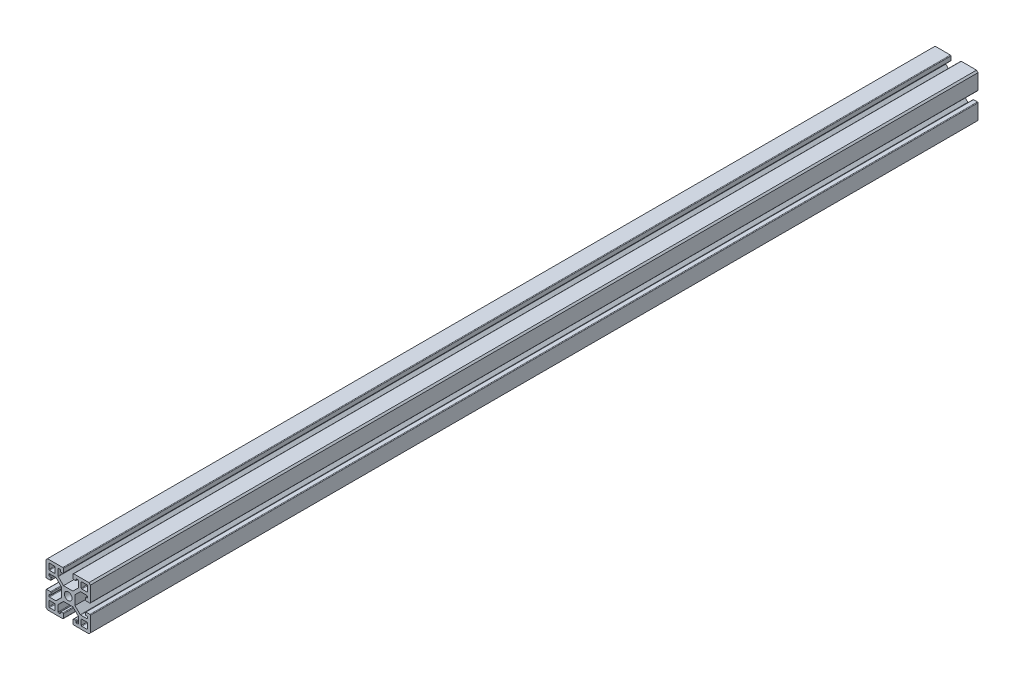
SolidWorks part; units mm, degrees
ref_plane "Front" through (0, 0, 0) normal (0, 0, 1) x (1, 0, 0)
ref_plane "Top" through (0, 0, 0) normal (0, 1, 0) x (1, 0, 0)
ref_plane "Right" through (0, 0, 0) normal (1, 0, 0) x (0, 0, -1)
sketch "Sketch1" plane through (0, 0, 0) normal (0, 0, 1) x (1, 0, 0)
  line L0 (4.699, 19.05) -> (17.78, 19.05)
  line L1 (4.191, 15.24) -> (4.191, 18.542)
  line L2 (6.223, 14.732) -> (4.699, 14.732)
  line L3 (6.731, 16.002) -> (6.731, 15.24)
  line L4 (0, 0) -> (18.415, 18.415) construction
  line L5 (8.1534, 16.51) -> (7.239, 16.51)
  line L6 (8.6614, 10.6679) -> (8.6614, 16.002)
  line L7 (4.0459, 5.842) -> (8.5126, 10.3087)
  line L8 (-4.0459, 5.842) -> (4.0459, 5.842)
  line L9 (11.2014, 16.002) -> (11.2014, 11.7094)
  line L10 (16.002, 16.51) -> (11.7094, 16.51)
  line L11 (-19.05, 17.78) -> (-17.78, 19.05)
  line L12 (-19.05, 4.699) -> (-19.05, 17.78)
  line L13 (-15.24, 4.191) -> (-18.542, 4.191)
  line L14 (16.51, 16.002) -> (16.51, 11.7094)
  line L15 (16.002, 11.2014) -> (11.7094, 11.2014)
  line L16 (-14.732, 6.223) -> (-14.732, 4.699)
  line L17 (-16.002, 6.731) -> (-15.24, 6.731)
  line L18 (-16.51, 8.1534) -> (-16.51, 7.239)
  line L19 (-10.6679, 8.6614) -> (-16.002, 8.6614)
  line L20 (-5.842, 4.0459) -> (-10.3087, 8.5126)
  line L21 (-5.842, -4.0459) -> (-5.842, 4.0459)
  line L22 (-16.002, 11.2014) -> (-11.7094, 11.2014)
  line L23 (-16.51, 16.002) -> (-16.51, 11.7094)
  line L24 (-16.002, 16.51) -> (-11.7094, 16.51)
  line L25 (-11.2014, 16.002) -> (-11.2014, 11.7094)
  line L26 (-4.0459, 5.842) -> (-8.5126, 10.3087)
  line L27 (-8.6614, 10.6679) -> (-8.6614, 16.002)
  line L28 (-8.1534, 16.51) -> (-7.239, 16.51)
  line L29 (-6.731, 16.002) -> (-6.731, 15.24)
  line L30 (-6.223, 14.732) -> (-4.699, 14.732)
  line L31 (-4.191, 15.24) -> (-4.191, 18.542)
  line L32 (0, 0) -> (0, 21.3525) construction
  line L33 (0, 0) -> (24.5779, 0) construction
  line L34 (-4.699, 19.05) -> (-17.78, 19.05)
  line L35 (19.05, -17.78) -> (17.78, -19.05)
  line L36 (19.05, -4.699) -> (19.05, -17.78)
  line L37 (15.24, -4.191) -> (18.542, -4.191)
  line L38 (14.732, -6.223) -> (14.732, -4.699)
  line L39 (16.002, -6.731) -> (15.24, -6.731)
  line L40 (16.51, -8.1534) -> (16.51, -7.239)
  line L41 (10.6679, -8.6614) -> (16.002, -8.6614)
  line L42 (5.842, -4.0459) -> (10.3087, -8.5126)
  line L43 (-4.699, -19.05) -> (-17.78, -19.05)
  line L44 (-4.191, -15.24) -> (-4.191, -18.542)
  line L45 (-6.223, -14.732) -> (-4.699, -14.732)
  line L46 (-6.731, -16.002) -> (-6.731, -15.24)
  line L47 (-8.1534, -16.51) -> (-7.239, -16.51)
  line L48 (-8.6614, -10.6679) -> (-8.6614, -16.002)
  line L49 (-4.0459, -5.842) -> (-8.5126, -10.3087)
  line L50 (-11.2014, -16.002) -> (-11.2014, -11.7094)
  line L51 (-16.002, -16.51) -> (-11.7094, -16.51)
  line L52 (-16.51, -16.002) -> (-16.51, -11.7094)
  line L53 (-16.002, -11.2014) -> (-11.7094, -11.2014)
  line L54 (-5.842, -4.0459) -> (-10.3087, -8.5126)
  line L55 (-10.6679, -8.6614) -> (-16.002, -8.6614)
  line L56 (-16.51, -8.1534) -> (-16.51, -7.239)
  line L57 (-16.002, -6.731) -> (-15.24, -6.731)
  line L58 (-14.732, -6.223) -> (-14.732, -4.699)
  line L59 (16.002, -11.2014) -> (11.7094, -11.2014)
  line L60 (16.51, -16.002) -> (16.51, -11.7094)
  line L61 (-15.24, -4.191) -> (-18.542, -4.191)
  line L62 (-19.05, -4.699) -> (-19.05, -17.78)
  line L63 (-19.05, -17.78) -> (-17.78, -19.05)
  line L64 (16.002, -16.51) -> (11.7094, -16.51)
  line L65 (11.2014, -16.002) -> (11.2014, -11.7094)
  line L66 (-4.0459, -5.842) -> (4.0459, -5.842)
  line L67 (4.0459, -5.842) -> (8.5126, -10.3087)
  line L68 (8.6614, -10.6679) -> (8.6614, -16.002)
  line L69 (8.1534, -16.51) -> (7.239, -16.51)
  line L70 (6.731, -16.002) -> (6.731, -15.24)
  line L71 (6.223, -14.732) -> (4.699, -14.732)
  line L72 (4.191, -15.24) -> (4.191, -18.542)
  line L73 (4.699, -19.05) -> (17.78, -19.05)
  line L134 (5.842, -4.0459) -> (5.842, 4.0459)
  line L135 (5.842, 4.0459) -> (10.3087, 8.5126)
  line L136 (10.6679, 8.6614) -> (16.002, 8.6614)
  line L137 (16.51, 8.1534) -> (16.51, 7.239)
  line L138 (16.002, 6.731) -> (15.24, 6.731)
  line L139 (14.732, 6.223) -> (14.732, 4.699)
  line L140 (15.24, 4.191) -> (18.542, 4.191)
  line L141 (19.05, 4.699) -> (19.05, 17.78)
  line L142 (19.05, 17.78) -> (17.78, 19.05)
  arc A0 (4.191, 18.542) -> (4.699, 19.05) centre (4.699, 18.542) cw
  circle A1 centre (0, 0) radius 3.302
  arc A2 (4.699, 14.732) -> (4.191, 15.24) centre (4.699, 15.24) cw
  arc A3 (6.731, 15.24) -> (6.223, 14.732) centre (6.223, 15.24) cw
  arc A4 (6.731, 16.002) -> (7.239, 16.51) centre (7.239, 16.002) cw
  arc A5 (8.1534, 16.51) -> (8.6614, 16.002) centre (8.1534, 16.002) cw
  arc A6 (8.6614, 10.6679) -> (8.5126, 10.3087) centre (8.1534, 10.6679) cw
  arc A7 (11.2014, 16.002) -> (11.7094, 16.51) centre (11.7094, 16.002) cw
  arc A8 (-18.542, 4.191) -> (-19.05, 4.699) centre (-18.542, 4.699) cw
  arc A9 (-14.732, 4.699) -> (-15.24, 4.191) centre (-15.24, 4.699) cw
  arc A10 (-15.24, 6.731) -> (-14.732, 6.223) centre (-15.24, 6.223) cw
  arc A11 (-16.002, 6.731) -> (-16.51, 7.239) centre (-16.002, 7.239) cw
  arc A12 (-16.51, 8.1534) -> (-16.002, 8.6614) centre (-16.002, 8.1534) cw
  arc A13 (-10.6679, 8.6614) -> (-10.3087, 8.5126) centre (-10.6679, 8.1534) cw
  arc A14 (11.2014, 11.7094) -> (11.7094, 11.2014) centre (11.7094, 11.7094) ccw
  arc A15 (-16.002, 11.2014) -> (-16.51, 11.7094) centre (-16.002, 11.7094) cw
  arc A16 (16.51, 16.002) -> (16.002, 16.51) centre (16.002, 16.002) ccw
  arc A17 (16.002, 11.2014) -> (16.51, 11.7094) centre (16.002, 11.7094) ccw
  arc A18 (-16.51, 16.002) -> (-16.002, 16.51) centre (-16.002, 16.002) cw
  arc A19 (-11.2014, 11.7094) -> (-11.7094, 11.2014) centre (-11.7094, 11.7094) cw
  arc A20 (-11.2014, 16.002) -> (-11.7094, 16.51) centre (-11.7094, 16.002) ccw
  arc A21 (-8.6614, 10.6679) -> (-8.5126, 10.3087) centre (-8.1534, 10.6679) ccw
  arc A22 (-8.1534, 16.51) -> (-8.6614, 16.002) centre (-8.1534, 16.002) ccw
  arc A23 (-6.731, 16.002) -> (-7.239, 16.51) centre (-7.239, 16.002) ccw
  arc A24 (-6.731, 15.24) -> (-6.223, 14.732) centre (-6.223, 15.24) ccw
  arc A25 (-4.699, 14.732) -> (-4.191, 15.24) centre (-4.699, 15.24) ccw
  arc A26 (-4.191, 18.542) -> (-4.699, 19.05) centre (-4.699, 18.542) ccw
  arc A27 (18.542, -4.191) -> (19.05, -4.699) centre (18.542, -4.699) cw
  arc A28 (14.732, -4.699) -> (15.24, -4.191) centre (15.24, -4.699) cw
  arc A29 (15.24, -6.731) -> (14.732, -6.223) centre (15.24, -6.223) cw
  arc A30 (16.002, -6.731) -> (16.51, -7.239) centre (16.002, -7.239) cw
  arc A31 (16.51, -8.1534) -> (16.002, -8.6614) centre (16.002, -8.1534) cw
  arc A32 (10.6679, -8.6614) -> (10.3087, -8.5126) centre (10.6679, -8.1534) cw
  arc A33 (-4.191, -18.542) -> (-4.699, -19.05) centre (-4.699, -18.542) cw
  arc A34 (-4.699, -14.732) -> (-4.191, -15.24) centre (-4.699, -15.24) cw
  arc A35 (-6.731, -15.24) -> (-6.223, -14.732) centre (-6.223, -15.24) cw
  arc A36 (-6.731, -16.002) -> (-7.239, -16.51) centre (-7.239, -16.002) cw
  arc A37 (-8.1534, -16.51) -> (-8.6614, -16.002) centre (-8.1534, -16.002) cw
  arc A38 (-8.6614, -10.6679) -> (-8.5126, -10.3087) centre (-8.1534, -10.6679) cw
  arc A39 (-11.2014, -16.002) -> (-11.7094, -16.51) centre (-11.7094, -16.002) cw
  arc A40 (-11.2014, -11.7094) -> (-11.7094, -11.2014) centre (-11.7094, -11.7094) ccw
  arc A41 (-16.51, -16.002) -> (-16.002, -16.51) centre (-16.002, -16.002) ccw
  arc A42 (16.002, -11.2014) -> (16.51, -11.7094) centre (16.002, -11.7094) cw
  arc A43 (16.51, -16.002) -> (16.002, -16.51) centre (16.002, -16.002) cw
  arc A44 (-16.002, -11.2014) -> (-16.51, -11.7094) centre (-16.002, -11.7094) ccw
  arc A45 (11.2014, -11.7094) -> (11.7094, -11.2014) centre (11.7094, -11.7094) cw
  arc A46 (-10.6679, -8.6614) -> (-10.3087, -8.5126) centre (-10.6679, -8.1534) ccw
  arc A47 (-16.51, -8.1534) -> (-16.002, -8.6614) centre (-16.002, -8.1534) ccw
  arc A48 (-16.002, -6.731) -> (-16.51, -7.239) centre (-16.002, -7.239) ccw
  arc A49 (-15.24, -6.731) -> (-14.732, -6.223) centre (-15.24, -6.223) ccw
  arc A50 (-14.732, -4.699) -> (-15.24, -4.191) centre (-15.24, -4.699) ccw
  arc A51 (-18.542, -4.191) -> (-19.05, -4.699) centre (-18.542, -4.699) ccw
  arc A52 (11.2014, -16.002) -> (11.7094, -16.51) centre (11.7094, -16.002) ccw
  arc A53 (8.6614, -10.6679) -> (8.5126, -10.3087) centre (8.1534, -10.6679) ccw
  arc A54 (8.1534, -16.51) -> (8.6614, -16.002) centre (8.1534, -16.002) ccw
  arc A55 (6.731, -16.002) -> (7.239, -16.51) centre (7.239, -16.002) ccw
  arc A56 (6.731, -15.24) -> (6.223, -14.732) centre (6.223, -15.24) ccw
  arc A57 (4.699, -14.732) -> (4.191, -15.24) centre (4.699, -15.24) ccw
  arc A58 (4.191, -18.542) -> (4.699, -19.05) centre (4.699, -18.542) ccw
  arc A109 (10.6679, 8.6614) -> (10.3087, 8.5126) centre (10.6679, 8.1534) ccw
  arc A110 (16.51, 8.1534) -> (16.002, 8.6614) centre (16.002, 8.1534) ccw
  arc A111 (16.002, 6.731) -> (16.51, 7.239) centre (16.002, 7.239) ccw
  arc A112 (15.24, 6.731) -> (14.732, 6.223) centre (15.24, 6.223) ccw
  arc A113 (14.732, 4.699) -> (15.24, 4.191) centre (15.24, 4.699) ccw
  arc A114 (18.542, 4.191) -> (19.05, 4.699) centre (18.542, 4.699) ccw
  point P104 (0, 5.842)
  point P207 (0, -5.842)
  point P211 (5.842, 0)
  point P214 (-5.842, 0)
  dimension "D1" = 6.604
  dimension "D3" = 0.508
  dimension "D2" = 38.1
  dimension "D4" = 8.382
  dimension "D5" = 14.732
  dimension "D6" = 17.3228
  dimension "D7" = 22.4028
  dimension "D8" = 33.02
  dimension "D10" = 11.684
  dimension "D11" = 4.0459
  dimension "D13" = 17.78
  dimension "D14" = 2.54
  dimension "D15" = 1.778
extrude "Extrude1" add sketch "Sketch1" along normal blind 762
sketch "Sketch2" plane through (19.05, 0, 0) normal (1, 0, 0) x (0, 0, -1)
  line L0 (-266.7, -19.05) -> (-304.8, 19.05)
  line L1 (-304.8, 19.05) -> (0, 19.05) construction
  line L2 (-304.8, 19.05) -> (-304.8, -19.05)
  line L3 (-304.8, -19.05) -> (0, -19.05) construction
  line L4 (-304.8, -19.05) -> (-266.7, -19.05)
  line L5 (-304.8, 4.699) -> (-304.8, 17.78) construction
  line L6 (-152.4, 17.78) -> (-152.4, 171.9297) construction
  line L7 (-304.8, 17.78) -> (0, 17.78) construction
  line L8 (0, -19.05) -> (-38.1, -19.05)
  line L9 (0, 19.05) -> (0, -19.05)
  line L10 (-38.1, -19.05) -> (0, 19.05)
  dimension "D1" = 45
extrude "Cut-Extrude1" cut sketch "Sketch2" against normal through all
